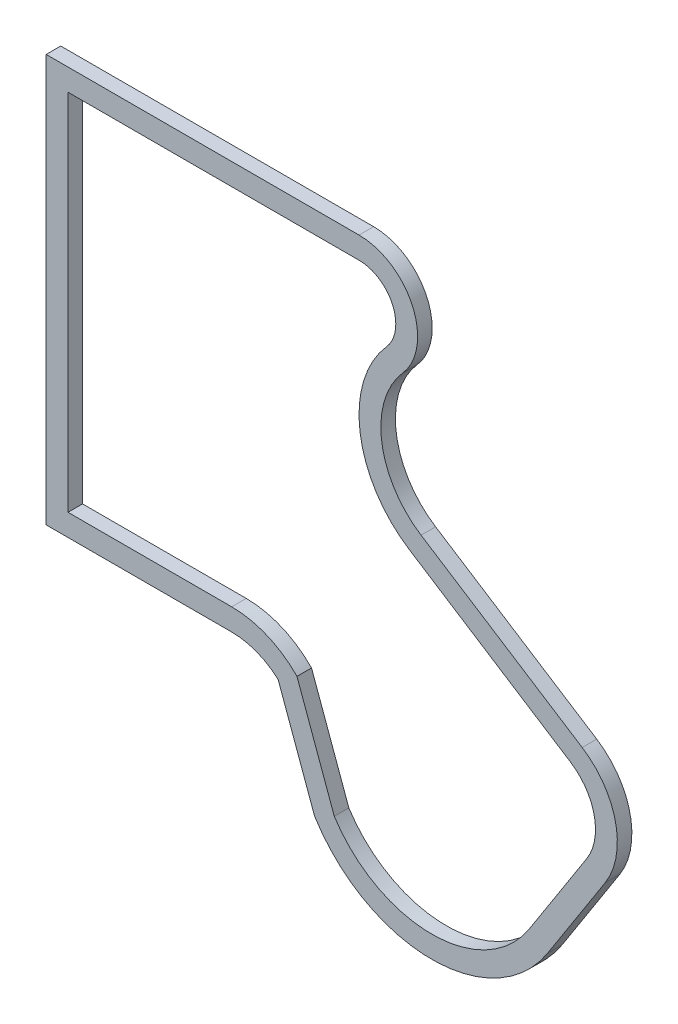
SolidWorks part; units mm, degrees
ref_plane "Front Plane" through (0, 0, 0) normal (0, 0, 1) x (1, 0, 0)
ref_plane "Top Plane" through (0, 0, 0) normal (0, 1, 0) x (1, 0, 0)
ref_plane "Right Plane" through (0, 0, 0) normal (1, 0, 0) x (0, 0, -1)
sketch "Sketch1" plane through (0, 0, 0) normal (0, 0, 1) x (1, 0, 0)
  line L0 (0, 0) -> (0, 127)
  line L1 (0, 127) -> (101.6, 127)
  line L2 (101.6, 127) -> (101.6, 175.337) construction
  line L3 (139.7, 80.3679) -> (194.9929, 30.5819) construction
  line L4 (0, 0) -> (57.15, 0)
  line L5 (79.933, -9.6367) -> (92.964, -45.439)
  line L6 (91.1321, 44.512) -> (91.1321, 7.5666) construction
  line L7 (119.1339, 48.2954) -> (175.3831, 12.2262)
  line L8 (161.036, -45.439) -> (181.1362, -14.0931)
  line L9 (101.6, 114.1681) -> (101.6, 2.8902) construction
  line L10 (-7.62, -7.62) -> (-7.62, 134.62)
  line L11 (-7.62, 134.62) -> (101.6, 134.62)
  line L12 (123.2471, 54.7099) -> (179.4963, 18.6407)
  line L13 (167.4505, -49.5523) -> (187.5507, -18.2063)
  line L14 (73.3702, -13.8849) -> (86.0802, -48.8055)
  line L15 (-7.62, -7.62) -> (57.15, -7.62)
  arc A0 (101.6, 127) -> (111.199, 105.6523) centre (101.6, 114.1681) cw
  arc A1 (111.199, 105.6523) -> (119.1339, 48.2954) centre (139.7, 80.3679) ccw
  arc A2 (57.15, 0) -> (79.933, -9.6367) centre (57.15, -31.75) cw
  arc A3 (92.964, -45.439) -> (161.036, -45.439) centre (127, -23.6138) ccw
  arc A4 (175.3831, 12.2262) -> (181.1362, -14.0931) centre (165.1, -3.81) cw
  arc A5 (101.6, 134.62) -> (116.8992, 100.5954) centre (101.6, 114.1681) cw
  arc A6 (116.8992, 100.5954) -> (123.2471, 54.7099) centre (139.7, 80.3679) ccw
  arc A7 (179.4963, 18.6407) -> (187.5507, -18.2063) centre (165.1, -3.81) cw
  arc A8 (86.0802, -48.8055) -> (167.4505, -49.5523) centre (127, -23.6138) ccw
  arc A9 (57.15, -7.62) -> (73.3702, -13.8849) centre (57.15, -31.75) cw
  point P7 (0, 0)
  point P14 (0, 0)
  point P23 (0, 0)
  point P25 (94.0644, -88.4722)
  point P26 (0, 0)
  point P27 (0, 0)
  point P28 (0, 0)
  point P29 (165.1, -3.81)
  point P30 (0, 0)
  dimension "D1" = 101.6
  dimension "D5" = 31.75
  dimension "D11" = 19.05
  dimension "D2" = 127
  dimension "D3" = 139.7
  dimension "D4" = 132
  dimension "D6" = 57.15
  dimension "D7" = 127
  dimension "D8" = 165.1
  dimension "D9" = 20
  dimension "D10" = 38.1
  dimension "D12" = 130.81
  dimension "D13" = 92.964
  dimension "D14" = 7.62
extrude "Boss-Extrude1" add sketch "Sketch1" along normal blind 5.08
